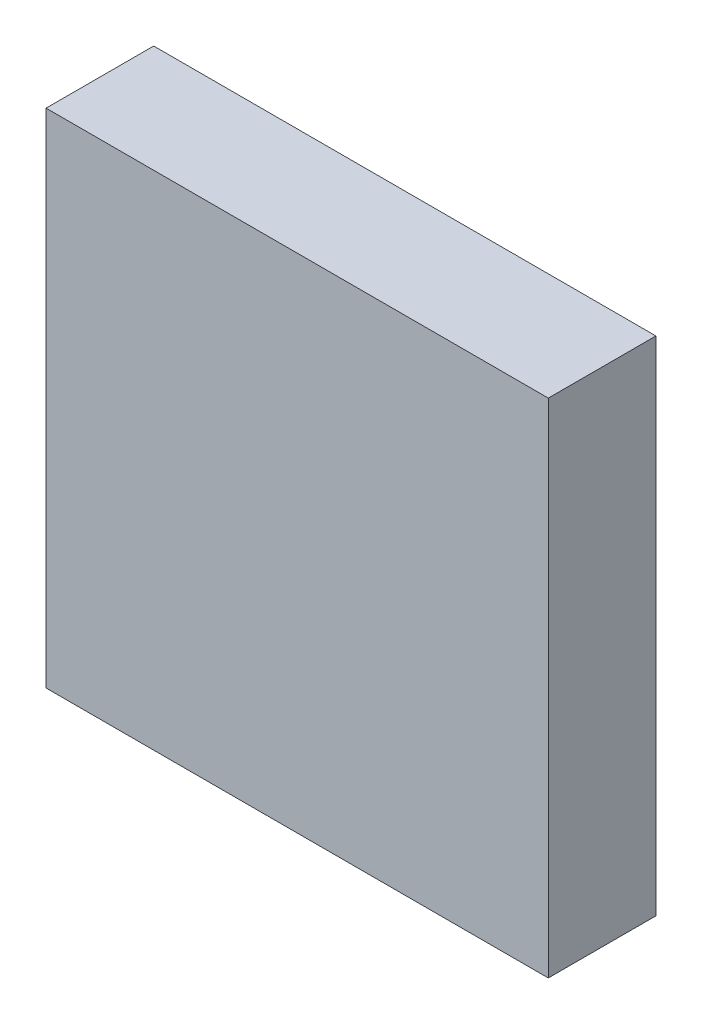
SolidWorks part; units mm, degrees
ref_plane "Front Plane" through (0, 0, 0) normal (0, 0, 1) x (1, 0, 0)
ref_plane "Top Plane" through (0, 0, 0) normal (0, 1, 0) x (1, 0, 0)
ref_plane "Right Plane" through (0, 0, 0) normal (1, 0, 0) x (0, 0, -1)
sketch "Sketch1" plane through (0, 0, 0) normal (0, 0, 1) x (1, 0, 0)
  line L1 (-7, 7) -> (7, 7)
  line L2 (-7, 7) -> (-7, -7)
  line L3 (-7, -7) -> (7, -7)
  line L4 (7, 7) -> (7, -7)
  line L5 (-7, 7) -> (7, -7) construction
  line L6 (-7, -7) -> (7, 7) construction
  point P0 (0, 0)
  dimension "D1" = 14
extrude "Boss-Extrude1" add sketch "Sketch1" along normal blind 3
